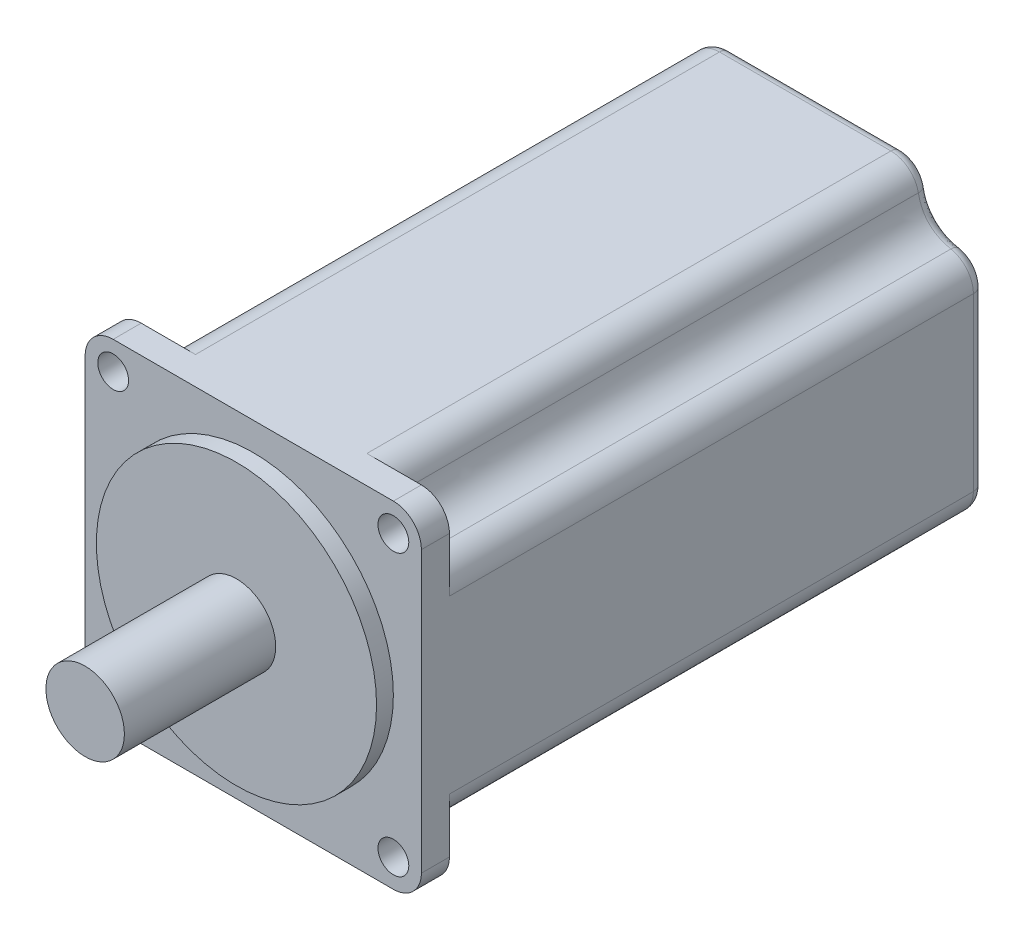
SolidWorks part; units mm, degrees
ref_plane "Front Plane" through (0, 0, 0) normal (0, 0, 1) x (1, 0, 0)
ref_plane "Top Plane" through (0, 0, 0) normal (0, 1, 0) x (1, 0, 0)
ref_plane "Right Plane" through (0, 0, 0) normal (1, 0, 0) x (0, 0, -1)
sketch "Sketch1" plane through (0, 0, 0) normal (0, 0, 1) x (1, 0, 0)
  line L1 (-30, 30) -> (30, 30)
  line L2 (-30, 30) -> (-30, -30)
  line L3 (-30, -30) -> (30, -30)
  line L4 (30, 30) -> (30, -30)
  line L5 (-30, 30) -> (30, -30) construction
  line L6 (-30, -30) -> (30, 30) construction
  circle A0 centre (-25, 25) radius 2.75
  circle A1 centre (25, 25) radius 2.75
  circle A2 centre (25, -25) radius 2.75
  circle A3 centre (-25, -25) radius 2.75
  point P0 (0, 0)
  point P17 (0, 0)
  dimension "D3" = 5.5
  dimension "D1" = 60
  dimension "D2" = 60
  dimension "D4" = 5
  dimension "D5" = 5
  dimension "D6" = 4
extrude "Boss-Extrude1" add sketch "Sketch1" along normal blind 5
sketch "Sketch2" plane through (0, 0, 5) normal (0, 0, 1) x (1, 0, 0)
  circle A0 centre (0, 0) radius 25
  dimension "D1" = 50
extrude "Boss-Extrude2" add sketch "Sketch2" along normal blind 3
sketch "Sketch3" plane through (0, 0, 8) normal (0, 0, 1) x (1, 0, 0)
  circle A0 centre (0, 0) radius 7
  dimension "D1" = 14
extrude "Boss-Extrude3" add sketch "Sketch3" along normal blind 27
sketch "Sketch4" plane through (0, 0, 0) normal (0, 0, -1) x (-1, 0, 0)
  line L0 (30, 30) -> (30, -30) construction
  line L1 (-30, 30) -> (30, 30) construction
  line L2 (30, -30) -> (-30, -30) construction
  line L3 (-30, -30) -> (-30, 30) construction
  line L4 (-20, 30) -> (20, 30)
  line L5 (30, 20) -> (30, -20)
  line L6 (20, -30) -> (-20, -30)
  line L7 (-30, -20) -> (-30, 20)
  spline S0 degree 2 poles (-30, 20) (-19.2026, 19.2985) (-20, 30) knots 0 0 0 1 1 1
  spline S1 degree 2 poles (20, 30) (19.2985, 19.2026) (30, 20) knots 0 0 0 1 1 1
  spline S2 degree 2 poles (30, -20) (19.2026, -19.2985) (20, -30) knots 0 0 0 1 1 1
  spline S3 degree 2 poles (-20, -30) (-19.2985, -19.2026) (-30, -20) knots 0 0 0 1 1 1
  point P21 (0, 0)
extrude "Boss-Extrude4" add sketch "Sketch4" along normal blind 95.5
fillet "Fillet1" radius 5 12 edges at (-30, 30, 2.5) (-30, -30, 2.5) (30, -30, 2.5) (30, 30, 2.5)
fillet "Fillet2" radius 2 16 edges at (-18.4718, 28.8689, -95.5) (-28.8666, 18.4491, -95.5) (-30, -0.0127, -95.5) (-28.8689, -18.4718, -95.5) (-18.4491, -28.8666, -95.5) (0.0127, -30, -95.5) (18.4718, -28.8689, -95.5) (28.8666, -18.4491, -95.5) (30, 0.0127, -95.5) (28.8689, 18.4718, -95.5) (18.4491, 28.8666, -95.5) (-0.0127, 30, -95.5)
